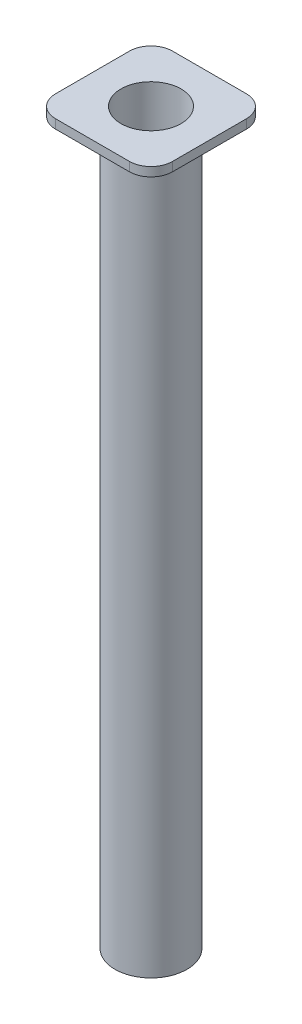
SolidWorks part; units mm, degrees
ref_plane "Front Plane" through (0, 0, 0) normal (0, 0, 1) x (1, 0, 0)
ref_plane "Top Plane" through (0, 0, 0) normal (0, 1, 0) x (1, 0, 0)
ref_plane "Right Plane" through (0, 0, 0) normal (1, 0, 0) x (0, 0, -1)
sketch "Sketch1" plane through (0, 0, 0) normal (0, 0, 1) x (1, 0, 0)
  line L0 (0, 0) -> (20, 0)
  line L1 (20, 0) -> (20, 405)
  line L2 (20, 405) -> (0, 405)
  line L3 (0, 405) -> (0, 0) construction
  line L4 (0, 0) -> (0, 405)
  dimension "D1" = 40
  dimension "D2" = 405
revolve "Revolve1" add sketch "Sketch1" angle 360 about L3
sketch "Sketch2" plane through (0, 405, 0) normal (0, 1, 0) x (1, 0, 0)
  line L1 (-20.5, -32.5) -> (20.5, -32.5)
  line L2 (-32.5, -20.5) -> (-32.5, 20.5)
  line L3 (-20.5, 32.5) -> (20.5, 32.5)
  line L4 (32.5, -20.5) -> (32.5, 20.5)
  line L5 (-32.5, -32.5) -> (32.5, 32.5) construction
  line L6 (-32.5, 32.5) -> (32.5, -32.5) construction
  arc A0 (-20.5, -32.5) -> (-32.5, -20.5) centre (-20.5, -20.5) cw
  arc A1 (20.5, -32.5) -> (32.5, -20.5) centre (20.5, -20.5) ccw
  arc A2 (20.5, 32.5) -> (32.5, 20.5) centre (20.5, 20.5) cw
  arc A3 (-32.5, 20.5) -> (-20.5, 32.5) centre (-20.5, 20.5) cw
  point P0 (0, 0)
  dimension "D2" = 12
  dimension "D1" = 65
extrude "Boss-Extrude1" add sketch "Sketch2" against normal blind 5
sketch "Sketch3" plane through (0, 0, 0) normal (0, -1, 0) x (1, 0, 0)
  circle A0 centre (0, 0) radius 16.7
  dimension "D1" = 33.4
extrude "Cut-Extrude1" cut sketch "Sketch3" against normal up to next
ref_plane "Plane1" through (0, 0, 0) normal (-0.7071, 0, 0.7071) x (0.7071, 0, 0.7071)
ref_plane "Plane2" through (0, 0, 0) normal (0.7071, 0, 0.7071) x (0.7071, 0, -0.7071)
